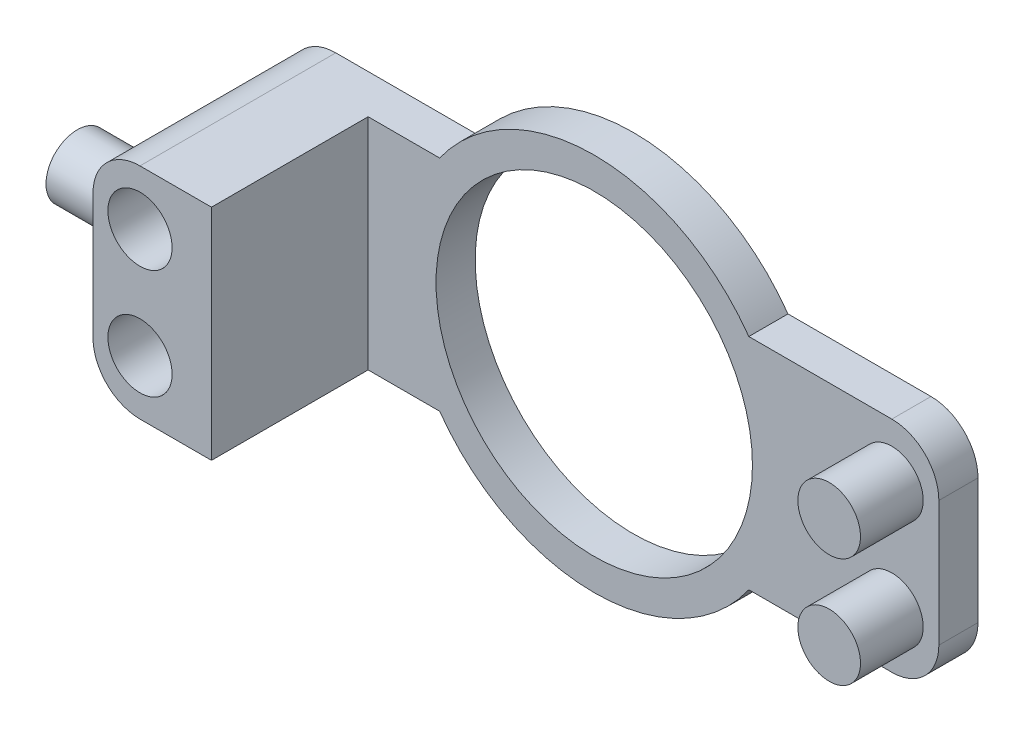
SolidWorks part; units mm, degrees
ref_plane "前视基准面" through (0, 0, 0) normal (0, 0, 1) x (1, 0, 0)
ref_plane "上视基准面" through (0, 0, 0) normal (0, 1, 0) x (1, 0, 0)
ref_plane "右视基准面" through (0, 0, 0) normal (1, 0, 0) x (0, 0, -1)
other "Configuration Table"
sketch "草图1" plane through (0, 0, 0) normal (0, 0, 1) x (1, 0, 0)
  line L1 (-22, -7) -> (22, -7)
  line L2 (-22, -7) -> (-22, 7)
  line L3 (-22, 7) -> (22, 7)
  line L4 (22, -7) -> (22, 7)
  line L5 (0, 7) -> (0, -7) construction
  line L6 (-22, 0) -> (22, 0) construction
  circle A0 centre (0, 0) radius 10.1
  circle A1 centre (0, 0) radius 12.1
  dimension "D1" = 20.2
  dimension "D2" = 2
  dimension "D3" = 7
  dimension "D4" = 22
extrude "凸台-拉伸1" add sketch "草图1" along normal blind 2.5 contours L3 A1 A0 | A1 L3 L2 L1 | A1 L1 L4 L3 | L1 A1 A0 | L3 A1 L1 A0 | L1 A1 L3 A0
fillet "圆角1" radius 3 4 edges at (22, 7, 1.25) (22, -7, 1.25) (-22, -7, 1.25) (-22, 7, 1.25)
sketch "草图2" plane through (0, 0, 2.5) normal (0, 0, 1) x (1, 0, 0)
  line L0 (-14.4348, 7) -> (-14.4348, -7)
  line L6 (22, -4) -> (22, 4)
  line L7 (19, 7) -> (9.8697, 7)
  line L8 (-9.8697, 7) -> (-19, 7)
  line L9 (-22, 4) -> (-22, -4)
  line L10 (-19, -7) -> (-9.8697, -7)
  line L11 (9.8697, -7) -> (19, -7)
  line L12 (22, -4) -> (22, 4)
  line L13 (19, 7) -> (9.8697, 7)
  line L14 (-9.8697, 7) -> (-19, 7)
  line L15 (-22, 4) -> (-22, -4)
  line L16 (-19, -7) -> (-9.8697, -7)
  line L17 (9.8697, -7) -> (19, -7)
  arc A6 (22, 4) -> (19, 7) centre (19, 4) ccw
  arc A7 (9.8697, 7) -> (-9.8697, 7) centre (0, 0) ccw
  arc A8 (-19, 7) -> (-22, 4) centre (-19, 4) ccw
  arc A9 (-22, -4) -> (-19, -7) centre (-19, -4) ccw
  arc A10 (-9.8697, -7) -> (9.8697, -7) centre (0, 0) ccw
  arc A11 (19, -7) -> (22, -4) centre (19, -4) ccw
  arc A12 (22, 4) -> (19, 7) centre (19, 4) ccw
  arc A13 (9.8697, 7) -> (-9.8697, 7) centre (0, 0) ccw
  arc A14 (-19, 7) -> (-22, 4) centre (-19, 4) ccw
  arc A15 (-22, -4) -> (-19, -7) centre (-19, -4) ccw
  arc A16 (-9.8697, -7) -> (9.8697, -7) centre (0, 0) ccw
  arc A17 (19, -7) -> (22, -4) centre (19, -4) ccw
  line M18 (-9.8697, 7) -> (-19, 7)
  arc M19 (-19, 7) -> (-22, 4) centre (-19, 4) ccw
  line M20 (-22, 4) -> (-22, -4)
  arc M21 (-22, -4) -> (-19, -7) centre (-19, -4) ccw
  line M22 (-19, -7) -> (-9.8697, -7)
  dimension "D1" = 0
extrude "凸台-拉伸2" add sketch "草图2" along normal blind 10 contours L0 M18 M19 M20 M21 M22
sketch "草图3" plane through (-22, 0, 0) normal (-1, 0, 0) x (0, 0, 1)
  line L0 (12.5, 7) -> (2.5, -7) construction
  line L1 (7.5, 0) -> (7.5, 10.5714) construction
  line L2 (2.5, 7) -> (12.5, -7) construction
  line L3 (0, 7) -> (12.5, 7)
  line L4 (0, 7) -> (0, -7)
  line L5 (0, -7) -> (12.5, -7)
  line L6 (12.5, 7) -> (12.5, -7)
  line L7 (15, 7) -> (15, -7)
  line L8 (0, 7) -> (15, -7)
  line L9 (2.5, 7) -> (2.5, 12.1) construction
  line L10 (2.5, 7) -> (2.5, 12.1) construction
  line L12 (0, 0) -> (15, 0) construction
  line L13 (7.5, 0) -> (7.5, 10.0687) construction
  circle A1 centre (7.5, 0) radius 2
  dimension "D1" = 4
extrude "凸台-拉伸3" add sketch "草图3" along normal blind 6 contours A1
sketch "草图4" plane through (0, 0, 0) normal (0, 0, -1) x (-1, 0, 0)
  line L0 (-19, 7) -> (-19, -7)
  line L1 (19, 7) -> (19, -7)
  line L2 (0, 0) -> (-28.2713, 0) construction
  arc A0 (-22, -4) -> (-19, -7) centre (-19, -4) ccw construction
  circle A1 centre (-19, 3.5) radius 2
  circle A2 centre (19, 3.5) radius 2
  circle A3 centre (19, -3.5) radius 2
  circle A4 centre (-19, -3.5) radius 2
  dimension "D1" = 4
  dimension "D2" = 3.5
  dimension "D3" = 4
  dimension "D4" = 3.5
sketch "草图5" plane through (0, 0, 2.5) normal (0, 0, 1) x (1, 0, 0)
  line L0 (0, 0) -> (0, 17.3916) construction
  line L6 (-9.8697, 7) -> (-14.4348, 7)
  line L7 (-14.4348, 7) -> (-14.4348, -7)
  line L8 (-14.4348, -7) -> (-9.8697, -7)
  line L9 (9.8697, -7) -> (19, -7)
  line L10 (22, -4) -> (22, 4)
  line L11 (19, 7) -> (9.8697, 7)
  line L12 (-9.8697, 7) -> (-14.4348, 7)
  line L13 (-14.4348, 7) -> (-14.4348, -7)
  line L14 (-14.4348, -7) -> (-9.8697, -7)
  line L15 (9.8697, -7) -> (19, -7)
  line L16 (22, -4) -> (22, 4)
  line L17 (19, 7) -> (9.8697, 7)
  circle A1 centre (-19, 3.5) radius 2
  circle A2 centre (-19, -3.5) radius 2
  circle A3 centre (19, -3.5) radius 2
  arc A4 (-9.8697, -7) -> (9.8697, -7) centre (0, 0) ccw
  arc A5 (19, -7) -> (22, -4) centre (19, -4) ccw
  arc A6 (22, 4) -> (19, 7) centre (19, 4) ccw
  arc A7 (9.8697, 7) -> (-9.8697, 7) centre (0, 0) ccw
  arc A8 (-9.8697, -7) -> (9.8697, -7) centre (0, 0) ccw
  arc A9 (19, -7) -> (22, -4) centre (19, -4) ccw
  arc A10 (22, 4) -> (19, 7) centre (19, 4) ccw
  arc A11 (9.8697, 7) -> (-9.8697, 7) centre (0, 0) ccw
  circle A12 centre (19, 3.5) radius 2
  dimension "D2" = 4
  dimension "D3" = 4
  dimension "D1" = 0
extrude "凸台-拉伸4" add sketch "草图5" along normal blind 4 contours A12 | A3
sketch "草图6" plane through (0, 0, 12.5) normal (0, 0, 1) x (1, 0, 0)
  circle A0 centre (-19, 3.5) radius 2.05
  circle A1 centre (-19, -3.5) radius 2.05
  dimension "D1" = 4.1
  dimension "D2" = 4.1
extrude "切除-拉伸1" cut sketch "草图6" against normal blind 4
fillet "圆角2" radius 1 1 edges at (-22, -2, 7.5)
